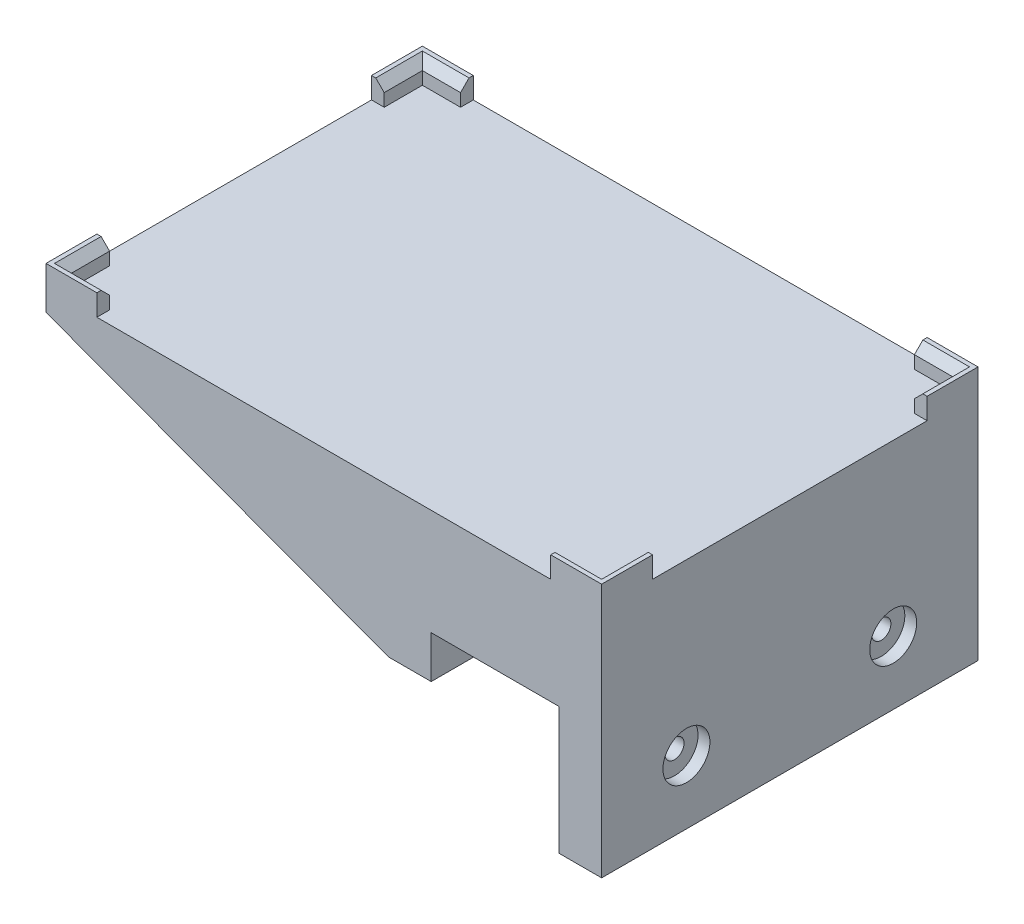
SolidWorks part; units mm, degrees
ref_plane "Front Plane" through (0, 0, 0) normal (0, 0, 1) x (1, 0, 0)
ref_plane "Top Plane" through (0, 0, 0) normal (0, 1, 0) x (1, 0, 0)
ref_plane "Right Plane" through (0, 0, 0) normal (1, 0, 0) x (0, 0, -1)
sketch "Sketch1" plane through (0, 0, 0) normal (0, 1, 0) x (1, 0, 0)
  line L1 (-65.53, -44.39) -> (65.53, -44.39)
  line L2 (-65.53, -44.39) -> (-65.53, 44.39)
  line L3 (-65.53, 44.39) -> (65.53, 44.39)
  line L4 (65.53, -44.39) -> (65.53, 44.39)
  line L5 (-65.53, -44.39) -> (65.53, 44.39) construction
  line L6 (-65.53, 44.39) -> (65.53, -44.39) construction
  point P0 (0, 0)
  dimension "D1" = 131.06
  dimension "D2" = 88.78
extrude "Boss-Extrude1" add sketch "Sketch1" along normal blind 5
sketch "Sketch2" plane through (0, 5, 0) normal (0, 1, 0) x (1, 0, 0)
  line L1 (-65.53, 44.39) -> (65.53, 44.39)
  line L2 (-65.53, 44.39) -> (-65.53, -44.39)
  line L3 (-65.53, -44.39) -> (65.53, -44.39)
  line L4 (65.53, 44.39) -> (65.53, -44.39)
  line L5 (-65.53, 44.39) -> (65.53, -44.39) construction
  line L6 (-65.53, -44.39) -> (65.53, 44.39) construction
  line L7 (-62.53, 41.39) -> (62.53, 41.39)
  line L8 (-62.53, 41.39) -> (-62.53, -41.39)
  line L9 (-62.53, -41.39) -> (62.53, -41.39)
  line L10 (62.53, 41.39) -> (62.53, -41.39)
  line L11 (-62.53, 41.39) -> (62.53, -41.39) construction
  line L12 (-62.53, -41.39) -> (62.53, 41.39) construction
  point P0 (0, 0)
  point P7 (0, 0)
  dimension "D1" = 3
  dimension "D2" = 3
extrude "Boss-Extrude2" add sketch "Sketch2" along normal blind 5
chamfer "Chamfer1" distance 2 angle 45 4 edges at (0, 10, 41.39) (62.53, 10, 0) (-62.53, 10, 0) (0, 10, -41.39)
sketch "Sketch3" plane through (0, 5, 0) normal (0, 1, 0) x (1, 0, 0)
  line L0 (-65.53, 32.39) -> (-65.53, -32.39)
  line L1 (-65.53, 44.39) -> (-65.53, -44.39) construction
  line L2 (-65.53, -32.39) -> (-53.53, -32.39)
  line L3 (-53.53, -32.39) -> (-53.53, -44.39)
  line L4 (-65.53, -44.39) -> (65.53, -44.39) construction
  line L5 (-53.53, -44.39) -> (53.53, -44.39)
  line L6 (53.53, -44.39) -> (53.53, -32.39)
  line L7 (53.53, -32.39) -> (65.53, -32.39)
  line L8 (65.53, -44.39) -> (65.53, 44.39) construction
  line L9 (65.53, -32.39) -> (65.53, 32.39)
  line L10 (65.53, 32.39) -> (53.53, 32.39)
  line L11 (53.53, 32.39) -> (53.53, 44.39)
  line L12 (65.53, 44.39) -> (-65.53, 44.39) construction
  line L13 (53.53, 44.39) -> (-53.53, 44.39)
  line L14 (-53.53, 44.39) -> (-53.53, 32.39)
  line L15 (-53.53, 32.39) -> (-65.53, 32.39)
  dimension "D1" = 12
extrude "Cut-Extrude1" cut sketch "Sketch3" along normal through all
sketch "Sketch4" plane through (0, 0, 0) normal (0, 0, 1) x (1, 0, 0)
  line L0 (65.53, 0) -> (65.53, -50)
  line L1 (65.53, -50) -> (55.53, -50)
  line L2 (55.53, -50) -> (55.53, -20)
  line L3 (55.53, -20) -> (25.33, -20)
  line L4 (25.33, -20) -> (25.33, -30)
  line L5 (25.33, -30) -> (15.33, -30)
  line L6 (15.33, -30) -> (15.33, 0)
  line L7 (-65.53, 0) -> (65.53, 0) construction
  line L8 (15.33, 0) -> (65.53, 0)
  dimension "D1" = 30.2
  dimension "D3" = 30
  dimension "D4" = 50
  dimension "D5" = 30
  dimension "D2" = 10
extrude "Boss-Extrude3" add sketch "Sketch4" along normal up to surface and the other way up to surface
sketch "Sketch5" plane through (0, 0, 44.39) normal (0, 0, 1) x (1, 0, 0)
  line L0 (-65.53, 0) -> (15.33, -30)
  line L1 (15.33, -30) -> (15.33, 0)
  line L2 (15.33, 0) -> (-65.53, 0)
extrude "Boss-Extrude4" add sketch "Sketch5" against normal blind 5
mirror "Mirror1" about plane through (0, 0, 0) normal (0, 0, 1) of "Boss-Extrude4"
sketch "Sketch18" plane through (65.53, 0, 0) normal (1, 0, 0) x (0, 0, -1)
  line L0 (-44.39, 10) -> (-44.39, -50) construction
  line L1 (0, 0) -> (0, -5.547) construction
  line L3 (-44.39, -50) -> (44.39, -50) construction
  point P0 (-24.39, -35)
  point P3 (24.39, -35)
  point P12 (0, 0)
  point P13 (0, 0)
  dimension "D1" = 20
  dimension "D2" = 15
hole_wizard "CBORE for M4 Hex Head Cap Screw1" positions "Sketch18" profile "Sketch17" counterbore size "M4" standard "ISO" end condition through all
sketch "Sketch17" plane through (65.53, -35, 24.39) normal (0, 1, 0) x (0, 0, -1)
  line L0 (0, 0) -> (0, 131.06)
  line L1 (0, 131.06) -> (2.25, 131.06)
  line L3 (2.25, 131.06) -> (2.25, 2.8)
  line L4 (2.25, 2.8) -> (5.5415, 2.8)
  line L5 (5.5415, 2.8) -> (5.5415, 0)
  line L7 (5.5415, 0) -> (0, 0)
  line L11 (0, -6.35) -> (0, 107.95) construction
  dimension "Thru Hole Dia." = 4.5
  dimension "Thru Hole Depth" = 131.06
  dimension "C'Bore Dia." = 11.083
  dimension "C'Bore Depth" = 2.8
equation "\"D2@Sketch2\"=\"D1@Sketch2\""
equation "\"D2@Sketch1\"=3 + 0.3 + 85.48"
equation "\"D1@Sketch1\"=3 + 0.3+ 127.76"
equation "\"D1@Sketch4\"=30 + 0.2"
equation "\"D4@Sketch4\"= 30 + 20"
equation "\"D5@Sketch4\"=30"
